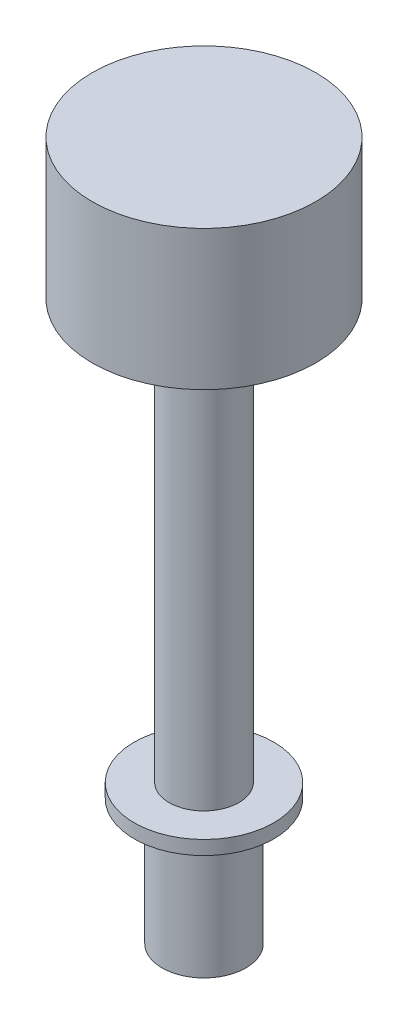
SolidWorks part; units mm, degrees
ref_plane "Front Plane" through (0, 0, 0) normal (0, 0, 1) x (1, 0, 0)
ref_plane "Top Plane" through (0, 0, 0) normal (0, 1, 0) x (1, 0, 0)
ref_plane "Right Plane" through (0, 0, 0) normal (1, 0, 0) x (0, 0, -1)
sketch "Sketch1" plane through (0, 0, 0) normal (0, 0, 1) x (1, 0, 0)
  line L0 (0, -10) -> (0, 40)
  line L1 (0, 40) -> (-8, 40)
  line L2 (-8, 40) -> (-8, 30)
  line L3 (-8, 30) -> (-2.5, 30)
  line L4 (-2.5, 30) -> (-2.5, 0)
  line L5 (-2.5, 0) -> (-5, 0)
  line L6 (-5, 0) -> (-5, -1)
  line L7 (-5, -1) -> (-3, -1)
  line L8 (-3, -1) -> (-3, -10)
  line L9 (-3, -10) -> (0, -10)
  dimension "D1" = 50
  dimension "D2" = 8
  dimension "D3" = 10
  dimension "D4" = 2.5
  dimension "D5" = 1
  dimension "D6" = 5
  dimension "D7" = 3
  dimension "D8" = 9
revolve "Revolve1" add sketch "Sketch1" angle 360 about L0
